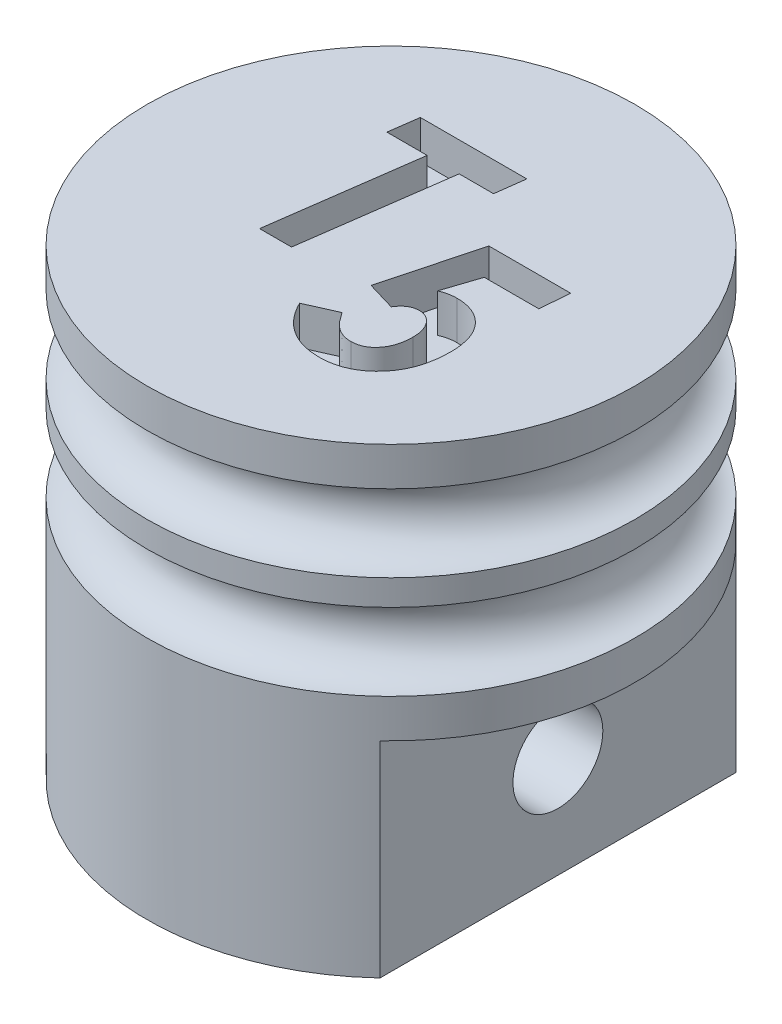
SolidWorks part; units mm, degrees
ref_plane "Alzado" through (0, 0, 0) normal (0, 0, 1) x (1, 0, 0)
ref_plane "Planta" through (0, 0, 0) normal (0, 1, 0) x (1, 0, 0)
ref_plane "Vista lateral" through (0, 0, 0) normal (1, 0, 0) x (0, 0, -1)
sketch "Sketch1" plane through (0, 0, 0) normal (0, 1, 0) x (1, 0, 0)
  circle A0 centre (0, 0) radius 9.5
  circle A1 centre (0, 0) radius 1.75
  dimension "D1" = 19
  dimension "D2" = 3.5
extrude "Boss-Extrude1" add sketch "Sketch1" along normal blind 18
sketch "Sketch2" plane through (0, 0, 0) normal (1, 0, 0) x (0, 0, -1)
  line L0 (-9.5, 18) -> (-9.5, 0) construction
  line L1 (9.5, 18) -> (-9.5, 18) construction
  line L2 (0, 18) -> (0, 0) construction
  circle A0 centre (-9.5, 15) radius 1.5
  circle A1 centre (-9.5, 11) radius 1.5
  dimension "D1" = 3
  dimension "D3" = 4
  dimension "D2" = 3
revolve "Cut-Revolve1" cut sketch "Sketch2" angle 360 about L2
sketch "Sketch3" plane through (0, 0, 0) normal (0, 0, 1) x (1, 0, 0)
  line L0 (-9.5, 0) -> (9.5, 0) construction
  line L1 (6.5, 0) -> (9.5, 0)
  line L2 (6.5, 0) -> (6.5, 8)
  line L3 (6.5, 8) -> (9.5, 8)
  line L4 (9.5, 0) -> (9.5, 8)
  line L5 (9.5, 0) -> (9.5, 9.5) construction
  dimension "D1" = 8
  dimension "D2" = 3
extrude "Cut-Extrude1" cut sketch "Sketch3" against normal through all both and the other way through all
sketch "Sketch4" plane through (0, 0, 0) normal (0, -1, 0) x (1, 0, 0)
  line L0 (6.5, -6.9282) -> (6.5, 6.9282) construction
  line L1 (0.5, 3) -> (3.5, 3)
  line L2 (0.5, 3) -> (0.5, -3)
  line L3 (0.5, -3) -> (3.5, -3)
  line L4 (3.5, 3) -> (3.5, -3)
  line L5 (0.5, 3) -> (3.5, -3) construction
  line L6 (0.5, -3) -> (3.5, 3) construction
  point P0 (2, 0)
  dimension "D1" = 3
  dimension "D2" = 6
  dimension "D3" = 3
extrude "Cut-Extrude2" cut sketch "Sketch4" against normal blind 8
sketch "Sketch5" plane through (6.5, 0, 0) normal (1, 0, 0) x (0, 0, -1)
  circle A0 centre (0, 4) radius 1.75
  dimension "D1" = 3.5
extrude "Cut-Extrude3" cut sketch "Sketch5" against normal up to next
sketch "Sketch6" plane through (0, 18, 0) normal (0, 1, 0) x (1, 0, 0)
  circle A0 centre (0, 0) radius 1.75
extrude "Boss-Extrude2" add sketch "Sketch6" against normal blind 8.5
sketch "Sketch7" plane through (0, 18, 0) normal (0, 1, 0) x (1, 0, 0)
  text T0 "<b><i>T</i></b>" font "Century Gothic" height in points 26
  text T1 "<b>5</b>" font "Century Gothic" height in points 26
  dimension "D1" = 4
extrude "Cut-Extrude4" cut sketch "Sketch7" against normal blind 1.5
